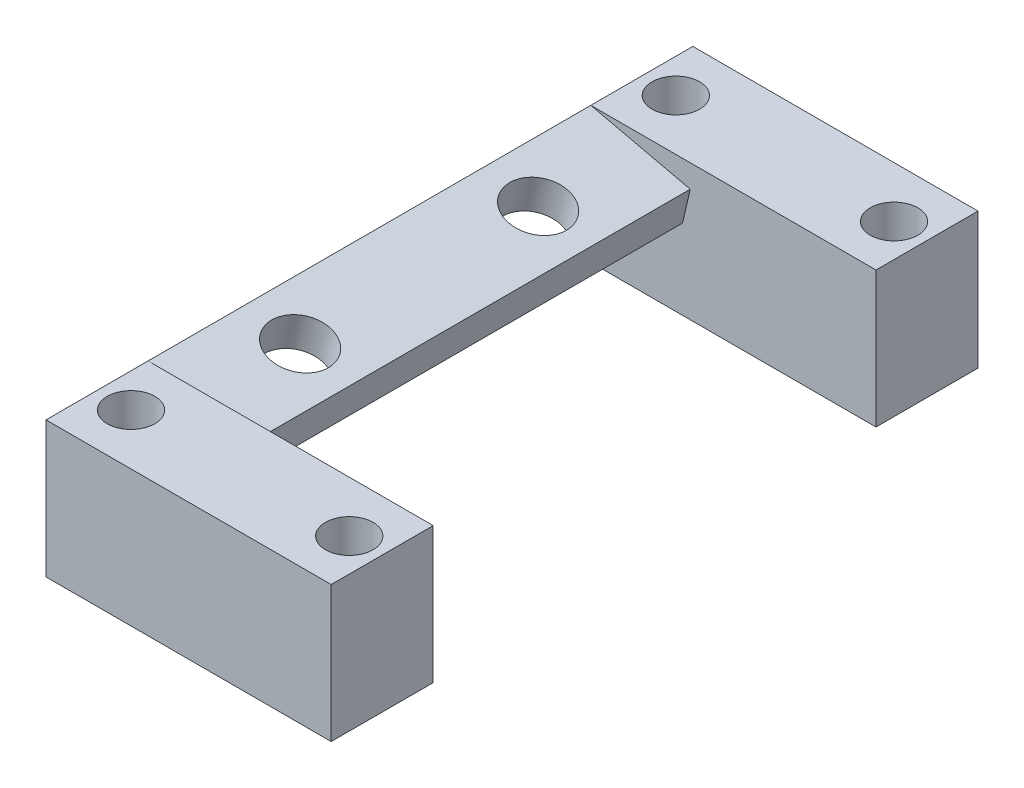
SolidWorks part; units mm, degrees
ref_plane "Front Plane" through (0, 0, 0) normal (0, 0, 1) x (1, 0, 0)
ref_plane "Top Plane" through (0, 0, 0) normal (0, 1, 0) x (1, 0, 0)
ref_plane "Right Plane" through (0, 0, 0) normal (1, 0, 0) x (0, 0, -1)
sketch "Sketch1" plane through (0, 0, 0) normal (0, 0, 1) x (1, 0, 0)
  line L1 (-35.7075, 20.8555) -> (-14.4075, 20.8555)
  line L2 (-35.7075, 20.8555) -> (-35.7075, 10.6955)
  line L3 (-35.7075, 10.6955) -> (-14.4075, 10.6955)
  line L4 (-14.4075, 20.8555) -> (-14.4075, 10.6955)
  dimension "D1" = 21.3
  dimension "D2" = 10.16
extrude "Boss-Extrude1" add sketch "Sketch1" along normal blind 7.62
sketch "Sketch2" plane through (0, 0, 0) normal (0, 0, -1) x (-1, 0, 0)
  line L1 (28.2828, 19.1414) -> (35.7075, 20.8555)
  line L2 (28.2828, 19.1414) -> (28.8542, 16.6665)
  line L3 (28.8542, 16.6665) -> (36.2789, 18.3806)
  line L4 (35.7075, 20.8555) -> (36.2789, 18.3806)
  dimension "D1" = 7.62
  dimension "D2" = 2.54
extrude "Boss-Extrude2" add sketch "Sketch2" along normal blind 33.0708
sketch "Sketch4" plane through (0, 0, -33.0708) normal (0, 0, -1) x (-1, 0, 0)
  line L1 (35.7075, 20.8555) -> (14.4075, 20.8555)
  line L2 (35.7075, 20.8555) -> (35.7075, 10.6955)
  line L3 (35.7075, 10.6955) -> (14.4075, 10.6955)
  line L4 (14.4075, 20.8555) -> (14.4075, 10.6955)
  dimension "D1" = 10.16
  dimension "D2" = 21.3
extrude "Boss-Extrude4" add sketch "Sketch4" along normal blind 7.62 separate body
sketch "Sketch5" plane through (0, 20.8555, 0) normal (0, 1, 0) x (1, 0, 0)
  line L0 (-14.4075, 0) -> (-35.7075, 0) construction
  line L1 (-35.7075, -7.62) -> (-35.7075, 0) construction
  circle A0 centre (-33.1675, -3.81) radius 1.778
  circle A1 centre (-16.8675, -3.81) radius 1.778
  point P8 (0, 0)
  point P10 (-33.3765, -3.6307)
  dimension "D1" = 3.81
  dimension "D3" = 3.556
  dimension "D4" = 16.3
  dimension "D2" = 2.54
  dimension "D5" = 3.81
extrude "Cut-Extrude1" cut sketch "Sketch5" against normal blind 10.16
sketch "Sketch6" plane through (0, 20.8555, 0) normal (0, 1, 0) x (1, 0, 0)
  line L0 (-35.7075, 40.6908) -> (-35.7075, 33.0708) construction
  line L1 (-35.7075, 33.0708) -> (-14.4075, 33.0708) construction
  circle A0 centre (-33.1675, 36.8808) radius 1.778
  circle A1 centre (-16.8675, 36.8808) radius 1.778
  dimension "D1" = 2.54
  dimension "D3" = 16.3
  dimension "D2" = 3.81
  dimension "D4" = 3.81
extrude "Cut-Extrude2" cut sketch "Sketch6" against normal blind 10.16
sketch "Sketch7" plane through (2.7643, 11.9736, 0) normal (0.225, 0.9744, 0) x (0.9744, -0.225, 0)
  line L0 (-39.4838, 33.0708) -> (-39.4838, 0) construction
  line L1 (-39.4838, 0) -> (-31.8638, 0) construction
  circle A0 centre (-35.6738, 7.6454) radius 2.1717
  circle A1 centre (-35.6738, 25.4254) radius 2.1717
  point P10 (-35.1903, 25.4356)
  dimension "D1" = 3.81
  dimension "D3" = 17.78
  dimension "D2" = 7.6454
  dimension "D4" = 3.81
extrude "Cut-Extrude3" cut sketch "Sketch7" against normal blind 2.54
